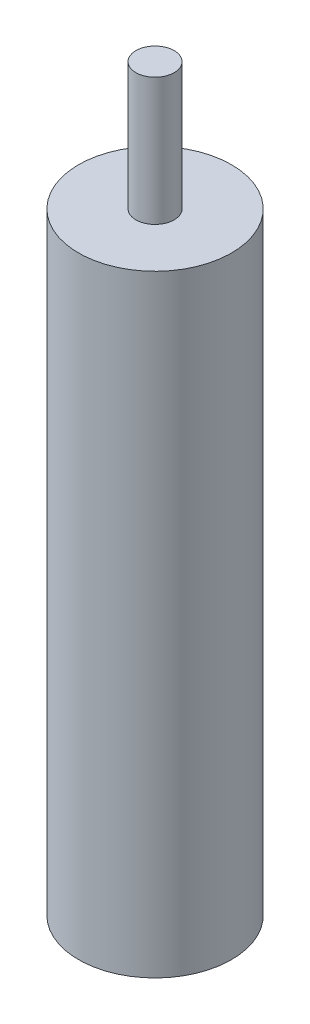
SolidWorks part; units mm, degrees
ref_plane "Front Plane" through (0, 0, 0) normal (0, 0, 1) x (1, 0, 0)
ref_plane "Top Plane" through (0, 0, 0) normal (0, 1, 0) x (1, 0, 0)
ref_plane "Right Plane" through (0, 0, 0) normal (1, 0, 0) x (0, 0, -1)
sketch "Sketch1" plane through (0, 0, 0) normal (0, 1, 0) x (1, 0, 0)
  circle A0 centre (0, 0) radius 0.5
  dimension "D1" = 1
extrude "Boss-Extrude1" add sketch "Sketch1" against normal blind 3.3333
sketch "Sketch2" plane through (0, -3.3333, 0) normal (0, -1, 0) x (1, 0, 0)
  circle A0 centre (0, 0) radius 2
  dimension "D1" = 4
extrude "Boss-Extrude2" add sketch "Sketch2" along normal blind 16
scale "Scale1" scale about centroid uniform scaling yes scale factor 2.5
sketch "Sketch3" plane through (0, -31.5197, 0) normal (0, -1, 0) x (1, 0, 0)
  circle A0 centre (0, 0) radius 5 construction
  point P0 (5, 0)
  point P1 (0, 0)
ref_plane "Plane1" through (-5, 0, 0) normal (1, 0, 0) x (0, 0, -1)
